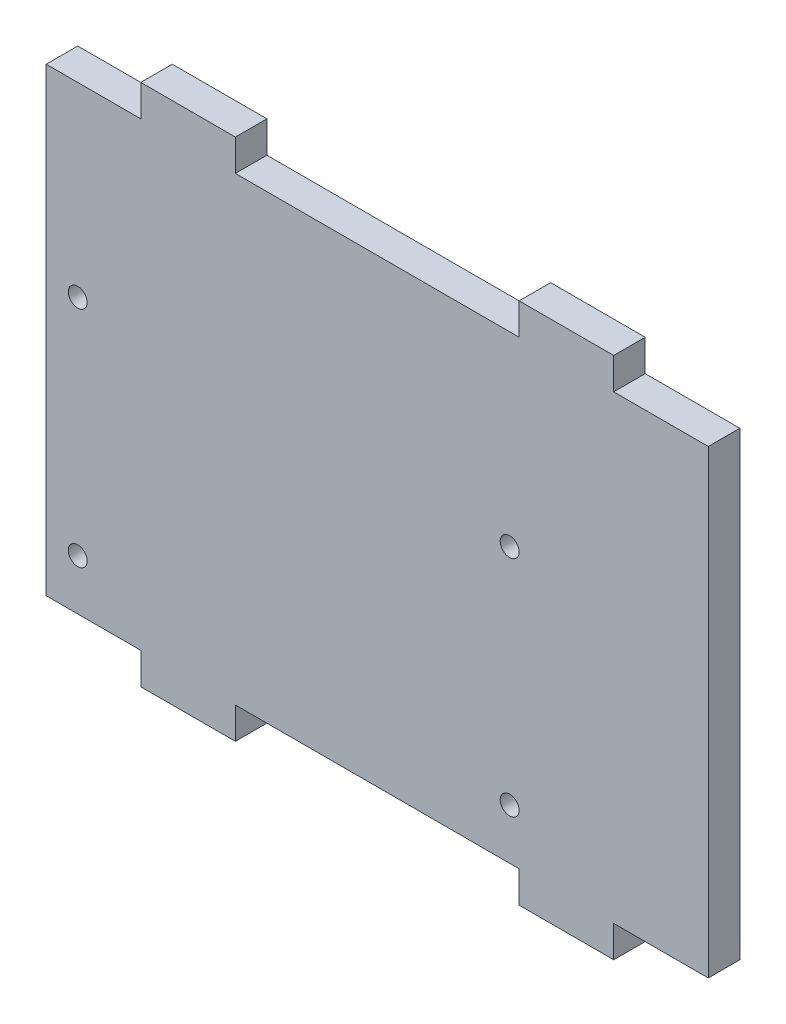
SolidWorks part; units mm, degrees
material "Balsa"
ref_plane "Plan de face" through (0, 0, 0) normal (0, 0, 1) x (1, 0, 0)
ref_plane "Plan de dessus" through (0, 0, 0) normal (0, 1, 0) x (1, 0, 0)
ref_plane "Plan de droite" through (0, 0, 0) normal (1, 0, 0) x (0, 0, -1)
sketch "Esquisse1" plane through (0, 0, 0) normal (0, 0, 1) x (1, 0, 0)
  line L1 (-174.8582, 152.0591) -> (-69.8582, 152.0591)
  line L2 (-174.8582, 152.0591) -> (-174.8582, 79.0591)
  line L3 (-174.8582, 79.0591) -> (-69.8582, 79.0591)
  line L4 (-69.8582, 152.0591) -> (-69.8582, 79.0591)
  dimension "D1" = 73
  dimension "D2" = 105
extrude "Boss.-Extru.1" add sketch "Esquisse1" along normal blind 5
sketch "Esquisse2" plane through (0, 0, 5) normal (0, 0, 1) x (1, 0, 0)
  line L0 (-101.3582, 122.5591) -> (-169.8582, 122.5591) construction
  line L1 (-169.8582, 122.5591) -> (-169.8582, 87.0591) construction
  line L2 (-169.8582, 87.0591) -> (-101.3582, 87.0591) construction
  line L3 (-101.3582, 87.0591) -> (-101.3582, 122.5591) construction
  line L4 (-174.8582, 79.0591) -> (-69.8582, 79.0591) construction
  line L5 (-174.8582, 152.0591) -> (-174.8582, 79.0591) construction
  circle A0 centre (-101.3582, 122.5591) radius 1.5
  circle A1 centre (-169.8582, 122.5591) radius 1.5
  circle A2 centre (-169.8582, 87.0591) radius 1.5
  circle A3 centre (-101.3582, 87.0591) radius 1.5
  dimension "D1" = 68.5
  dimension "D2" = 35.5
  dimension "D3" = 8
  dimension "D4" = 5
extrude "Enlèv. mat.-Extru.1" cut sketch "Esquisse2" against normal blind 5
sketch "Esquisse3" plane through (0, 0, 5) normal (0, 0, 1) x (1, 0, 0)
  line L0 (-174.8582, 79.0591) -> (-69.8582, 79.0591) construction
  line L1 (-159.8582, 79.0591) -> (-144.8582, 79.0591)
  line L2 (-159.8582, 79.0591) -> (-159.8582, 74.0591)
  line L3 (-159.8582, 74.0591) -> (-144.8582, 74.0591)
  line L4 (-144.8582, 79.0591) -> (-144.8582, 74.0591)
  line L5 (-69.8582, 79.0591) -> (-69.8582, 152.0591) construction
  line L6 (-99.8582, 79.0591) -> (-84.8582, 79.0591)
  line L7 (-99.8582, 79.0591) -> (-99.8582, 74.0591)
  line L8 (-99.8582, 74.0591) -> (-84.8582, 74.0591)
  line L9 (-84.8582, 79.0591) -> (-84.8582, 74.0591)
  line L10 (-174.8582, 115.5591) -> (-69.8582, 115.5591) construction
  line L11 (-174.8582, 152.0591) -> (-174.8582, 79.0591) construction
  line L12 (-84.8582, 152.0591) -> (-84.8582, 157.0591)
  line L13 (-99.8582, 157.0591) -> (-84.8582, 157.0591)
  line L14 (-99.8582, 152.0591) -> (-99.8582, 157.0591)
  line L15 (-99.8582, 152.0591) -> (-84.8582, 152.0591)
  line L16 (-144.8582, 152.0591) -> (-144.8582, 157.0591)
  line L17 (-159.8582, 157.0591) -> (-144.8582, 157.0591)
  line L18 (-159.8582, 152.0591) -> (-159.8582, 157.0591)
  line L19 (-159.8582, 152.0591) -> (-144.8582, 152.0591)
  dimension "D1" = 15
  dimension "D2" = 15
  dimension "D3" = 45
  dimension "D4" = 15
  dimension "D5" = 5
extrude "Boss.-Extru.2" add sketch "Esquisse3" against normal blind 5
